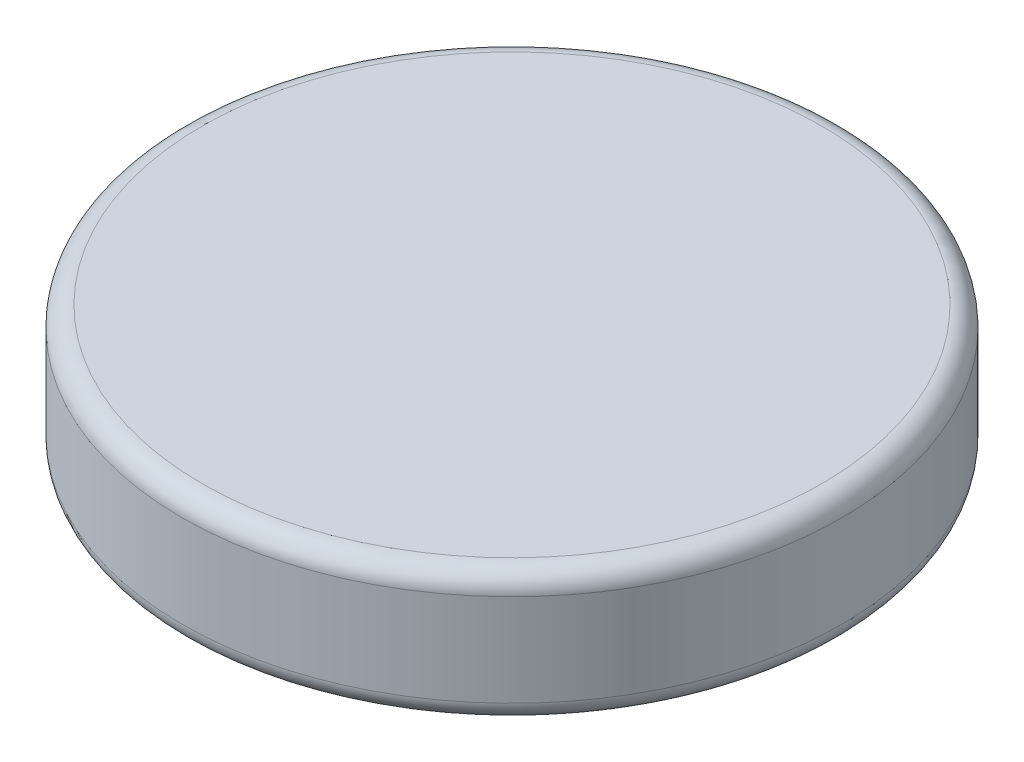
SolidWorks part; units mm, degrees
material "1060-H18"
ref_plane "Piano frontale" through (0, 0, 0) normal (0, 0, 1) x (1, 0, 0)
ref_plane "Piano superiore" through (0, 0, 0) normal (0, 1, 0) x (1, 0, 0)
ref_plane "Piano destro" through (0, 0, 0) normal (1, 0, 0) x (0, 0, -1)
sketch "Schizzo1" plane through (0, 0, 0) normal (0, 1, 0) x (1, 0, 0)
  circle A0 centre (0, 0) radius 5
  dimension "D1" = 10
extrude "Estrusione-Estrusione1" add sketch "Schizzo1" along normal blind 2
fillet "Raccordo1" radius 0.3 1 edges at (0, 2, 5)
fillet "Raccordo2" radius 0.3 1 edges at (0, 0, 5)
